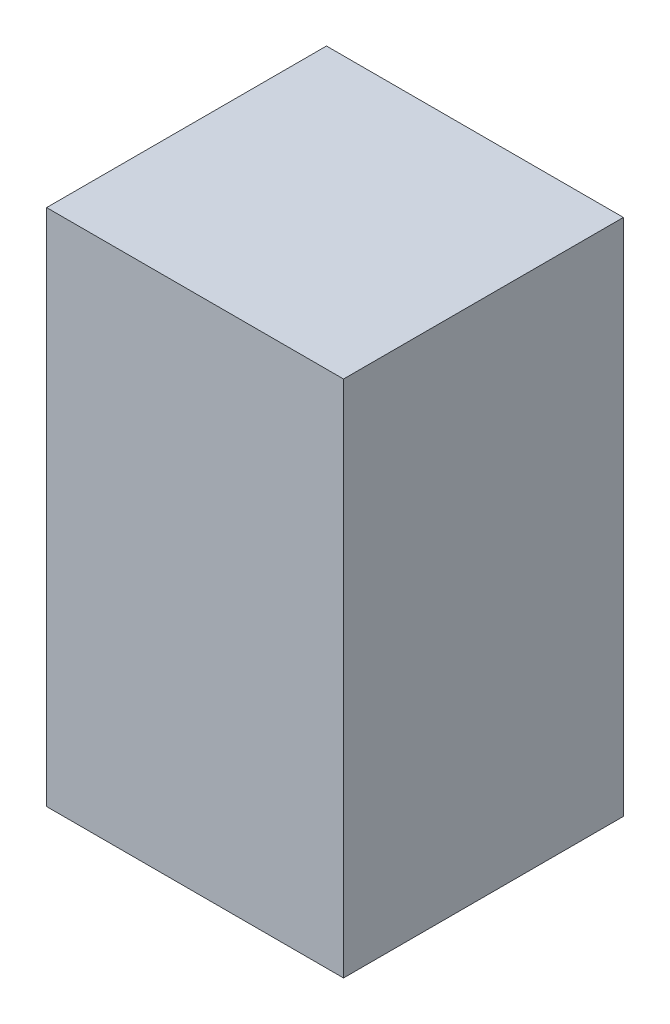
SolidWorks part; units mm, degrees
ref_plane "Front Plane" through (0, 0, 0) normal (0, 0, 1) x (1, 0, 0)
ref_plane "Top Plane" through (0, 0, 0) normal (0, 1, 0) x (1, 0, 0)
ref_plane "Right Plane" through (0, 0, 0) normal (1, 0, 0) x (0, 0, -1)
ref_plane "PL_Box_0_base" through (0, 0, 8) normal (0, 0, 1) x (1, 0, 0)
sketch "SK_Box_0" plane through (0, 0, 8) normal (0, 0, 1) x (1, 0, 0)
  line L0 (-43.5, -76) -> (43.5, -76)
  line L1 (43.5, -76) -> (43.5, 76)
  line L2 (43.5, 76) -> (-43.5, 76)
  line L3 (-43.5, 76) -> (-43.5, -76)
  dimension "P1" = 43.5
  dimension "P2" = 76
  dimension "P3" = 43.5
  dimension "P4" = 76
  dimension "P5" = 43.5
  dimension "P6" = 76
  dimension "P7" = 43.5
  dimension "P8" = 76
extrude "Box_0" add sketch "SK_Box_0" along normal blind 82
